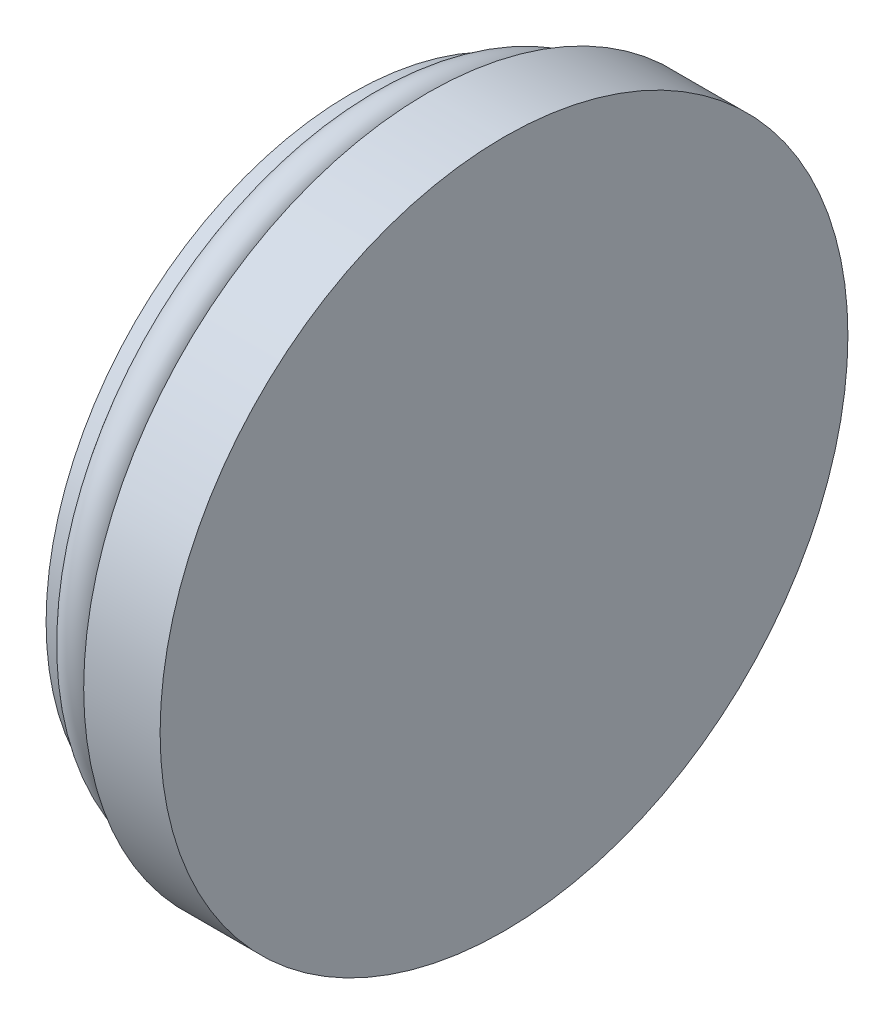
SolidWorks part; units mm, degrees
material "Acrylic (Medium-high impact)"
ref_plane "Front" through (0, 0, 0) normal (0, 0, 1) x (1, 0, 0)
ref_plane "Top" through (0, 0, 0) normal (0, 1, 0) x (1, 0, 0)
ref_plane "Right" through (0, 0, 0) normal (1, 0, 0) x (0, 0, -1)
sketch "Sketch1" plane through (0, 0, 0) normal (1, 0, 0) x (0, 0, -1)
  circle A0 centre (0, 0) radius 12.6746
  dimension "D1" = 25.3492
extrude "Boss-Extrude1" add sketch "Sketch1" along normal blind 3.175
sketch "Sketch2" plane through (3.175, 0, 0) normal (1, 0, 0) x (0, 0, -1)
  circle A0 centre (0, 0) radius 14.2875
  dimension "D1" = 28.575
extrude "Boss-Extrude2" add sketch "Sketch2" along normal blind 3.175
ref_plane "Plane1" through (6.1976, 0, 0) normal (0, -1, 0) x (0, 0, 1)
sketch "Sketch3" plane through (0, 0, 0) normal (0, 0, 1) x (1, 0, 0)
  line L0 (0, 0) -> (-3.5821, 0) construction
  line L6 (2.3812, 12.7) -> (2.3812, 11.9062)
  line L7 (2.3812, 11.9062) -> (0.7937, 11.9062)
  line L8 (0.7937, 11.9062) -> (0.7937, 12.7)
  arc A0 (2.3812, 12.7) -> (0.7937, 12.7) centre (1.5875, 12.7) ccw
  dimension "D1" = 1.5875
  dimension "D2" = 0.7937
  dimension "D3" = 25.4
revolve "Revolve1" add sketch "Sketch3" angle 360 about L0
sketch "Sketch4" plane through (0, 0, 0) normal (-1, 0, 0) x (0, 0, 1)
  circle A0 centre (0, 0) radius 10.033
  dimension "D1" = 20.066
split line "Split Line1"
